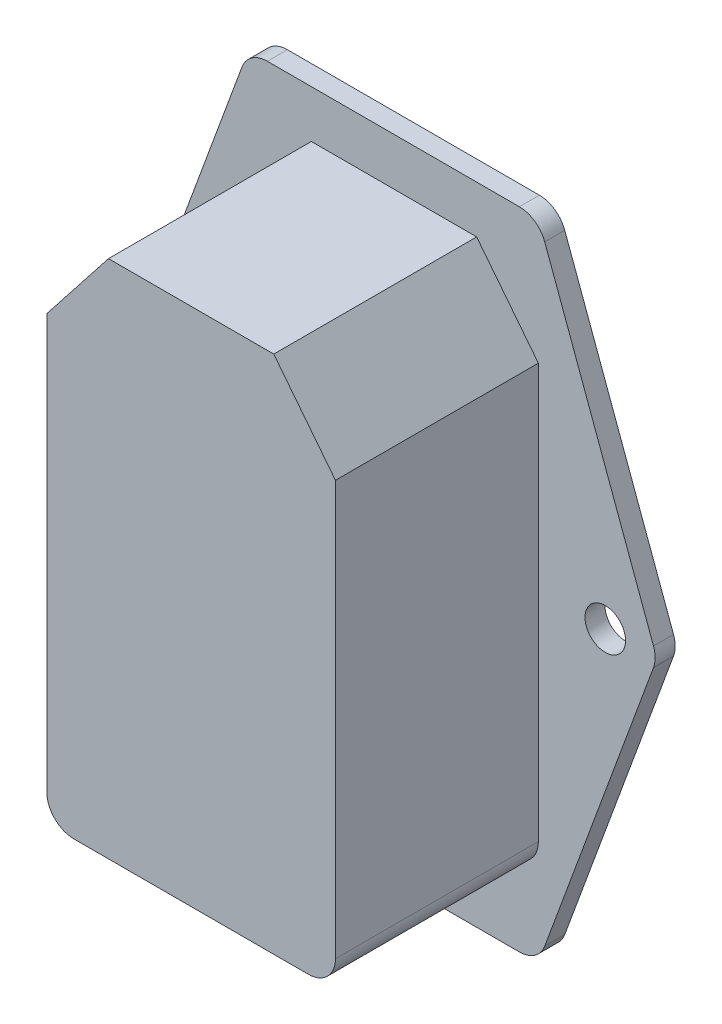
SolidWorks part; units mm, degrees
ref_plane "Front Plane" through (0, 0, 0) normal (0, 0, 1) x (1, 0, 0)
ref_plane "Top Plane" through (0, 0, 0) normal (0, 1, 0) x (1, 0, 0)
ref_plane "Right Plane" through (0, 0, 0) normal (1, 0, 0) x (0, 0, -1)
sketch "Sketch1" plane through (0, 0, 0) normal (0, 0, 1) x (1, 0, 0)
  line L0 (2.54, 0) -> (24.5618, 0)
  line L1 (27.1018, 2.54) -> (27.1018, 41.4401)
  line L2 (27.1018, 41.4401) -> (21.3106, 48.8095)
  line L3 (21.3106, 48.8095) -> (5.7912, 48.8095)
  line L4 (0, 2.54) -> (0, 41.4401)
  line L5 (0, 41.4401) -> (5.7912, 48.8095)
  arc A0 (2.54, 0) -> (0, 2.54) centre (2.54, 2.54) cw
  arc A1 (24.5618, 0) -> (27.1018, 2.54) centre (24.5618, 2.54) ccw
  point P10 (0, 0)
  point P13 (27.1018, 0)
  dimension "D5" = 2.54
  dimension "D7" = 2.54
  dimension "D1" = 27.1018
  dimension "D2" = 41.4401
  dimension "D3" = 9.3726
  dimension "D4" = 15.5194
  dimension "D6" = 9.3726
extrude "Boss-Extrude1" add sketch "Sketch1" along normal blind 19.05
sketch "Sketch2" plane through (0, 0, 0) normal (0, 0, 1) x (1, 0, 0)
  line L0 (1.6576, 53.2672) -> (25.3172, 53.2672)
  line L2 (27.1018, 2.54) -> (27.1018, 41.4401) construction
  line L3 (0, 41.4401) -> (0, 2.54) construction
  line L4 (21.3106, 48.8095) -> (5.7912, 48.8095) construction
  line L7 (27.701, 51.6043) -> (37.9145, 23.8468)
  line L8 (37.9145, 22.0925) -> (27.701, -5.665)
  line L9 (25.3172, -7.3279) -> (1.6576, -7.3279)
  line L10 (-0.7262, -5.665) -> (-10.9397, 22.0925)
  line L11 (-10.9397, 23.8468) -> (-0.7262, 51.6043)
  line L12 (2.54, 0) -> (24.5618, 0) construction
  arc A0 (1.6576, -7.3279) -> (-0.7262, -5.665) centre (1.6576, -4.7879) cw
  arc A1 (-10.9397, 22.0925) -> (-10.9397, 23.8468) centre (-8.556, 22.9696) cw
  arc A2 (27.701, -5.665) -> (25.3172, -7.3279) centre (25.3172, -4.7879) cw
  arc A3 (37.9145, 22.0925) -> (37.9145, 23.8468) centre (35.5308, 22.9696) ccw
  arc A4 (27.701, 51.6043) -> (25.3172, 53.2672) centre (25.3172, 50.7272) ccw
  arc A5 (-0.7262, 51.6043) -> (1.6576, 53.2672) centre (1.6576, 50.7272) cw
  point P16 (27.1018, 21.9901)
  point P21 (-11.2625, 22.9696)
  point P26 (38.2373, 22.9696)
  point P29 (27.0891, 53.2672)
  point P32 (-0.1143, 53.2672)
  dimension "D7" = 2.54
  dimension "D1" = 27.2034
  dimension "D2" = 4.4577
  dimension "D3" = 5.7785
  dimension "D4" = 7.3279
  dimension "D5" = 11.1355
  dimension "D6" = 11.2625
extrude "Boss-Extrude2" add sketch "Sketch2" against normal blind 1.8796
sketch "Sketch6" plane through (0, 0, 0) normal (0, 0, 1) x (1, 0, 0)
  line L0 (1.6576, -7.3279) -> (25.3172, -7.3279) construction
  circle A0 centre (33.3845, 22.9696) radius 1.905
  circle A1 centre (-6.4097, 22.9696) radius 1.905
  arc A3 (37.9145, 22.0925) -> (37.9145, 23.8468) centre (35.5308, 22.9696) ccw construction
  arc A4 (-10.9397, 23.8468) -> (-10.9397, 22.0925) centre (-8.556, 22.9696) ccw construction
  point P9 (38.0708, 22.9696)
  point P13 (-11.096, 22.9696)
  dimension "D1" = 3.81
  dimension "D2" = 4.6863
  dimension "D3" = 4.6863
  dimension "D4" = 30.2975
  dimension "D5" = 30.2975
extrude "Cut-Extrude1" cut sketch "Sketch6" against normal blind 20.4216 and the other way blind 22.606
